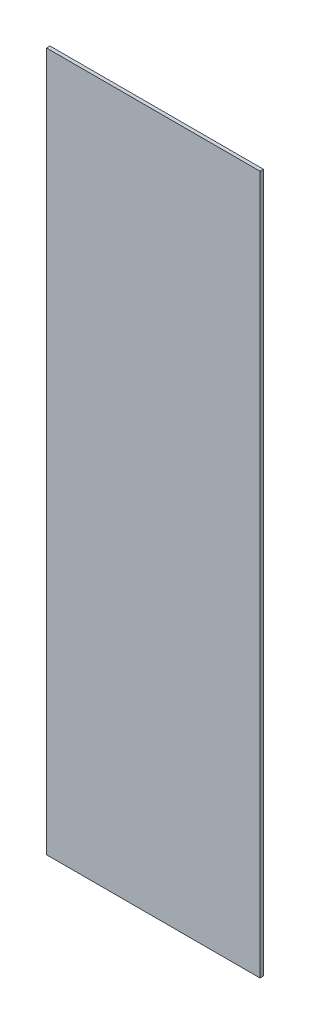
SolidWorks part; units mm, degrees
ref_plane "前视基准面" through (0, 0, 0) normal (0, 0, 1) x (1, 0, 0)
ref_plane "上视基准面" through (0, 0, 0) normal (0, 1, 0) x (1, 0, 0)
ref_plane "右视基准面" through (0, 0, 0) normal (1, 0, 0) x (0, 0, -1)
sketch "草图1" plane through (0, 0, 0) normal (0, 0, 1) x (1, 0, 0)
  line L1 (-62, 203) -> (62, 203)
  line L2 (-62, 203) -> (-62, -203)
  line L3 (-62, -203) -> (62, -203)
  line L4 (62, 203) -> (62, -203)
  line L5 (-62, 203) -> (62, -203) construction
  line L6 (-62, -203) -> (62, 203) construction
  point P1 (0, 0)
  dimension "D1" = 124
  dimension "D2" = 406
extrude "凸台-拉伸1" add sketch "草图1" along normal blind 2
